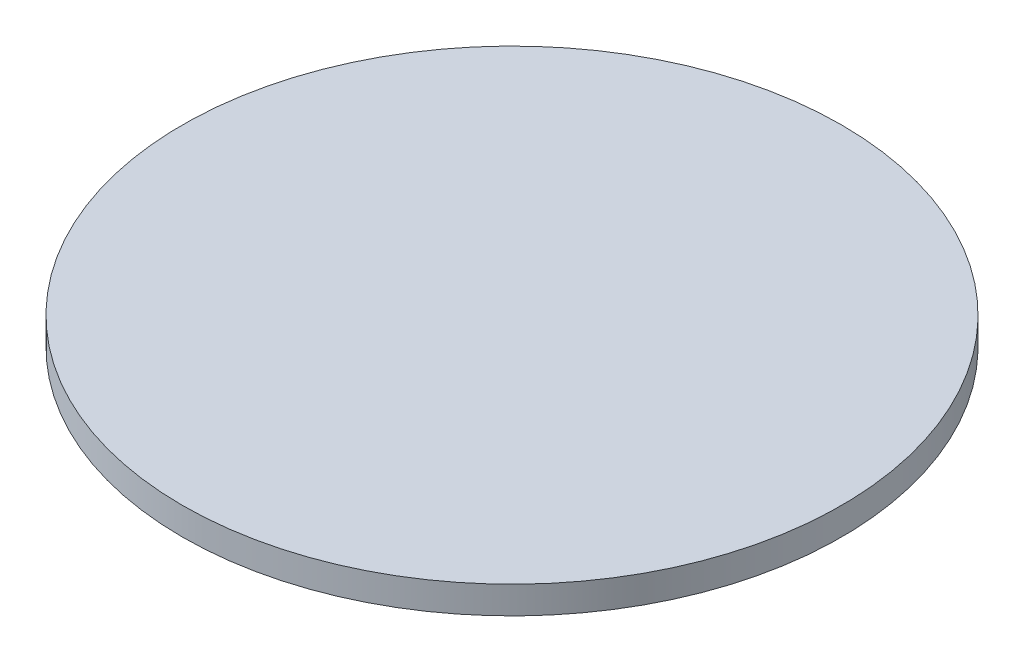
SolidWorks part; units mm, degrees
ref_plane "Front Plane" through (0, 0, 0) normal (0, 0, 1) x (1, 0, 0)
ref_plane "Top Plane" through (0, 0, 0) normal (0, 1, 0) x (1, 0, 0)
ref_plane "Right Plane" through (0, 0, 0) normal (1, 0, 0) x (0, 0, -1)
sketch "Sketch1" plane through (0, 0, 0) normal (0, 1, 0) x (1, 0, 0)
  circle A0 centre (0, 0) radius 38.1 construction
  point P3 (-38.1, 0)
  point P4 (38.1, 0)
  dimension "Diameter" = 76.2
sketch "Sketch2" plane through (0, 0, 0) normal (0, 0, 1) x (1, 0, 0)
  line L0 (-38.1, -1.5875) -> (-38.1, 1.5875) construction
  line L2 (-38.1, 1.5875) -> (38.1, 1.5875) construction
  line L3 (-38.1, -1.5875) -> (38.1, -1.5875) construction
  line L4 (38.1, 1.5875) -> (38.1, -1.5875) construction
  point P3 (-38.1, 0)
  dimension "Thickness" = 3.175
sketch "Sketch3" plane through (0, 0, 0) normal (0, 1, 0) x (1, 0, 0)
  circle A0 centre (0, 0) radius 38.1 construction
  circle A1 centre (0, 0) radius 38.1
extrude "Boss-Extrude1" add sketch "Sketch3" along normal up to vertex (1.5875 mm away) and the other way up to vertex (1.5875 mm away) up to point (-38.1, 1.5875, 0) other way up to point (-38.1, -1.5875, 0)
